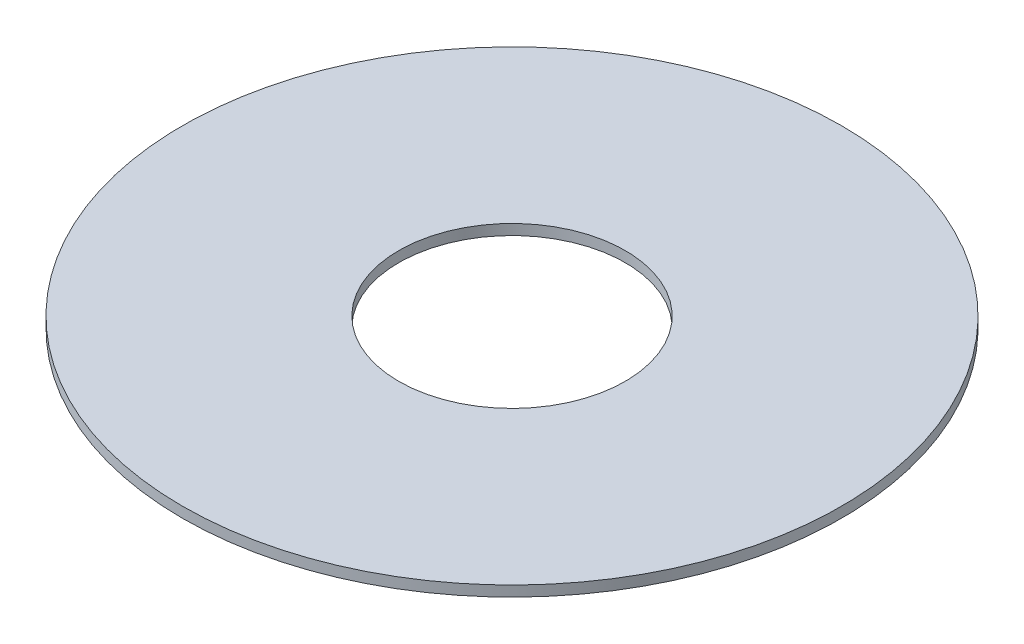
SolidWorks part; units mm, degrees
material "6061 Alloy"
ref_plane "Front Plane" through (0, 0, 0) normal (0, 0, 1) x (1, 0, 0)
ref_plane "Top Plane" through (0, 0, 0) normal (0, 1, 0) x (1, 0, 0)
ref_plane "Right Plane" through (0, 0, 0) normal (1, 0, 0) x (0, 0, -1)
sketch "Sketch1" plane through (0, 0, 0) normal (0, 1, 0) x (-1, 0, 0)
  circle A0 centre (-29.4585, -1.6977) radius 62.833
  circle A2 centre (-29.4585, -1.6977) radius 21.6
extrude "Boss-Extrude1" add sketch "Sketch1" along normal blind 2
